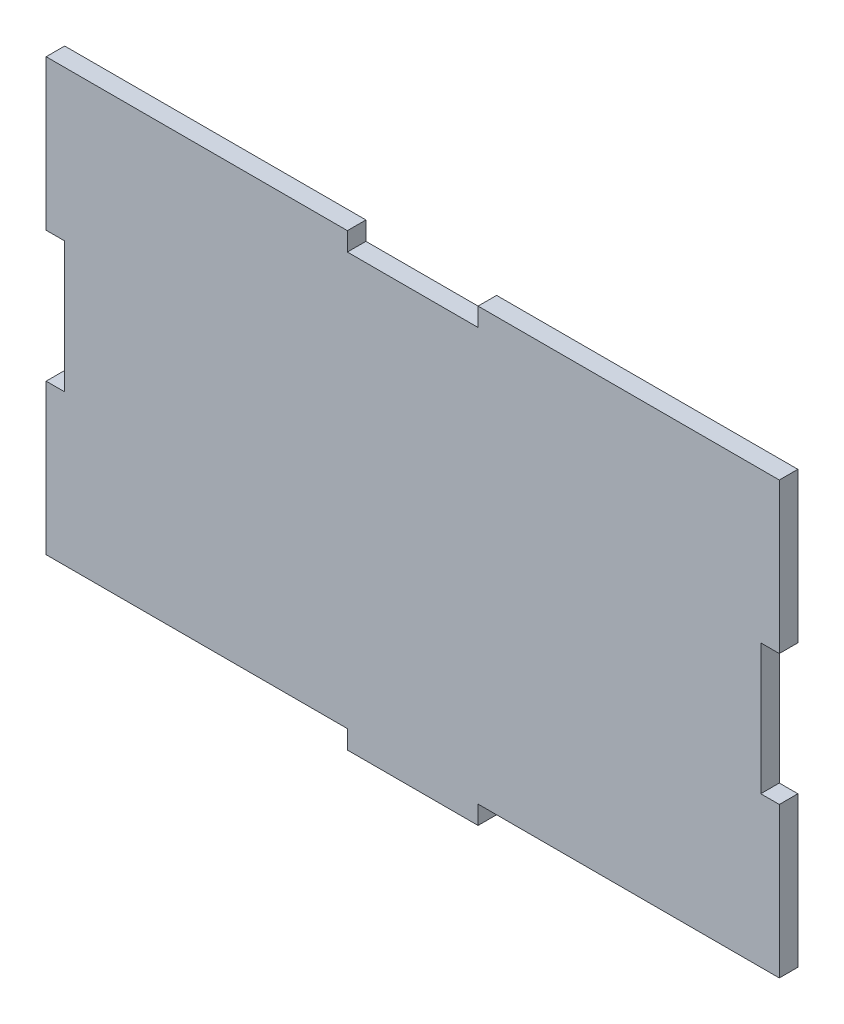
SolidWorks part; units mm, degrees
ref_plane "Front Plane" through (0, 0, 0) normal (0, 0, 1) x (1, 0, 0)
ref_plane "Top Plane" through (0, 0, 0) normal (0, 1, 0) x (1, 0, 0)
ref_plane "Right Plane" through (0, 0, 0) normal (1, 0, 0) x (0, 0, -1)
sketch "Sketch1" plane through (0, 0, 0) normal (0, 0, 1) x (1, 0, 0)
  line L0 (-85, 15.15) -> (-85, 50)
  line L1 (-85, -50) -> (-15.15, -50)
  line L2 (-85, -50) -> (-85, -15.15)
  line L3 (-85, 50) -> (-15.15, 50)
  line L4 (85, -50) -> (85, -15.15)
  line L5 (-85, -50) -> (85, 50) construction
  line L6 (-85, 50) -> (85, -50) construction
  line L8 (-15.15, 50) -> (-15.15, 45.7)
  line L9 (-15.15, 45.7) -> (15.15, 45.7)
  line L10 (15.15, 50) -> (15.15, 45.7)
  line L12 (15.15, -50) -> (15.15, -54.3)
  line L13 (15.15, -54.3) -> (-15.15, -54.3)
  line L14 (-15.15, -50) -> (-15.15, -54.3)
  line L15 (85, 15.15) -> (80.7, 15.15)
  line L17 (85, -15.15) -> (80.7, -15.15)
  line L18 (80.7, 15.15) -> (80.7, -15.15)
  line L19 (-85, 15.15) -> (-80.7, 15.15)
  line L21 (-85, -15.15) -> (-80.7, -15.15)
  line L22 (-80.7, 15.15) -> (-80.7, -15.15)
  line L23 (15.15, 50) -> (85, 50)
  line L24 (85, 15.15) -> (85, 50)
  line L25 (15.15, -50) -> (85, -50)
  point P0 (0, 0)
  point P22 (0, -54.3)
  point P23 (0, 45.7)
  point P24 (-80.7, 0)
  point P25 (80.7, 0)
  dimension "D1" = 170
  dimension "D2" = 100
  dimension "D3" = 30.3
  dimension "D4" = 4.3
extrude "Boss-Extrude1" add sketch "Sketch1" along normal blind 4.3
